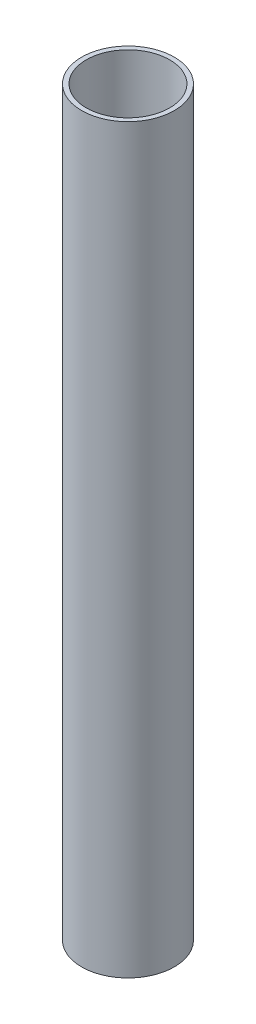
SolidWorks part; units mm, degrees
ref_plane "前视基准面" through (0, 0, 0) normal (0, 0, 1) x (1, 0, 0)
ref_plane "上视基准面" through (0, 0, 0) normal (0, 1, 0) x (1, 0, 0)
ref_plane "右视基准面" through (0, 0, 0) normal (1, 0, 0) x (0, 0, -1)
sketch "草图1" plane through (0, 0, 0) normal (0, 1, 0) x (1, 0, 0)
  circle A0 centre (0, 0) radius 10
  dimension "D1" = 20
extrude "1mm" add sketch "草图1" along normal mid plane 160 thin thin type one direction reverse wall 1
